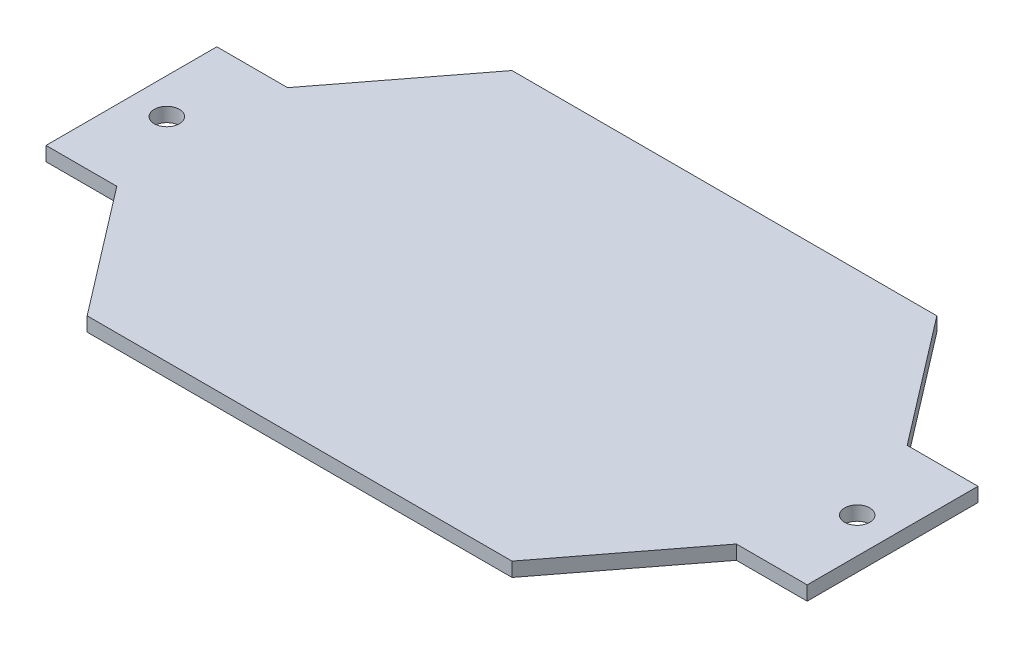
SolidWorks part; units mm, degrees
ref_plane "Front Plane" through (0, 0, 0) normal (0, 0, 1) x (1, 0, 0)
ref_plane "Top Plane" through (0, 0, 0) normal (0, 1, 0) x (1, 0, 0)
ref_plane "Right Plane" through (0, 0, 0) normal (1, 0, 0) x (0, 0, -1)
sketch "Sketch1" plane through (0, 0, 0) normal (0, 1, 0) x (1, 0, 0)
  line L0 (-6.35, 15.3192) -> (6.35, 15.3192)
  line L1 (6.35, 15.3192) -> (23.8125, 38.1)
  line L2 (23.8125, 38.1) -> (100.0125, 38.1)
  line L3 (100.0125, 38.1) -> (117.475, 15.3192)
  line L4 (117.475, 15.3192) -> (130.175, 15.3192)
  line L5 (130.175, 15.3192) -> (130.175, -15.3192)
  line L6 (130.175, -15.3192) -> (117.475, -15.3192)
  line L8 (100.0125, -38.1) -> (23.8125, -38.1)
  line L9 (23.8125, -38.1) -> (6.35, -15.3192)
  line L10 (6.35, -15.3192) -> (-6.35, -15.3192)
  line L11 (-6.35, -15.3192) -> (-6.35, 15.3192)
  line L12 (100.0125, -38.1) -> (117.475, -15.3192)
  line L13 (-6.35, 0) -> (0, 0) construction
  line L14 (0, -15.3192) -> (0, 0) construction
  line L15 (123.825, -15.3192) -> (123.825, 0) construction
  circle A0 centre (0, 0) radius 2.25
  circle A1 centre (123.825, 0) radius 2.25
  dimension "D2" = 4.5
  dimension "D1" = 123.825
  dimension "D3" = 6.35
  dimension "D4" = 76.2
  dimension "D5" = 76.2
extrude "Boss-Extrude1" add sketch "Sketch1" along normal blind 2.54
